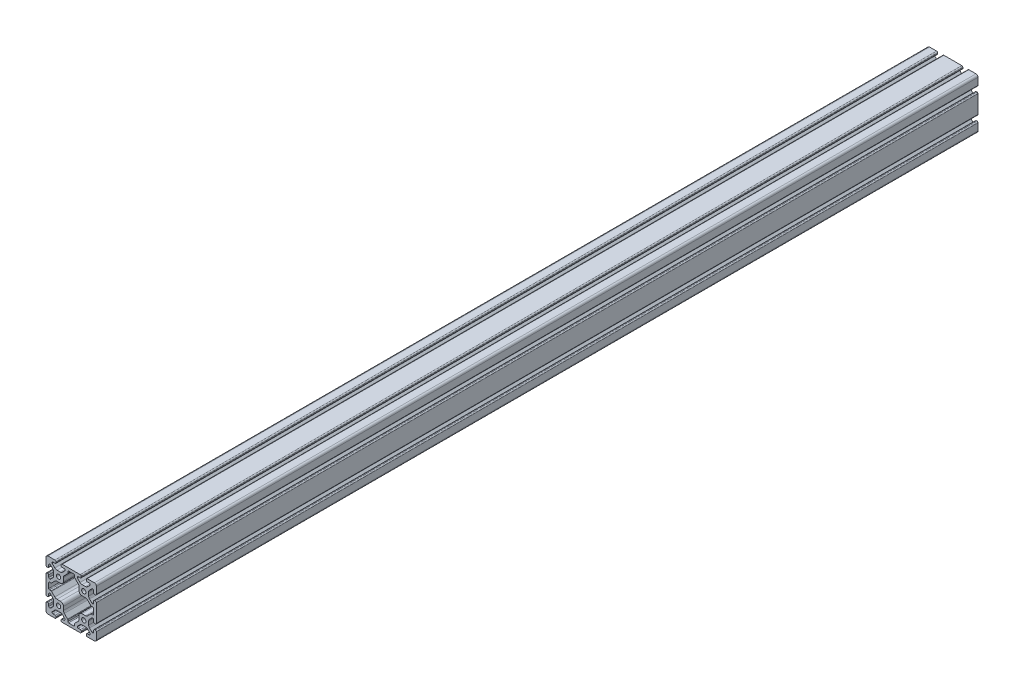
SolidWorks part; units mm, degrees
material "6061 Alloy"
ref_plane "Front Plane" through (0, 0, 0) normal (0, 0, 1) x (1, 0, 0)
ref_plane "Top Plane" through (0, 0, 0) normal (0, 1, 0) x (1, 0, 0)
ref_plane "Right Plane" through (0, 0, 0) normal (1, 0, 0) x (0, 0, -1)
sketch "Sketch1" plane through (0, 0, 0) normal (0, 0, 1) x (1, 0, 0)
  line L0 (0, -40) -> (0, 40) construction
  line L1 (0, 0) -> (-43.5804, 43.5804) construction
  line L2 (-20, 20) -> (-47.7323, 20) construction
  line L3 (-20, 20) -> (3.796, 43.796) construction
  line L4 (-20, 20) -> (-20, 43.5758) construction
  line L5 (-20, -27.7) -> (-20, -47.5576) construction
  line L7 (-36.8718, 24) -> (-28.8718, 24) construction
  line L8 (-36.8718, 24) -> (-36.8718, 16) construction
  line L9 (-36.8718, 16) -> (-28.8718, 16) construction
  line L10 (-28.8718, 24) -> (-28.8718, 16) construction
  line L11 (-36.8718, 24) -> (-28.8718, 16) construction
  line L12 (-36.8718, 16) -> (-28.8718, 24) construction
  line L131 (29.0912, 26.0365) -> (33.0827, 30.028)
  line L132 (27.7, 17.3222) -> (27.7, 22.6778)
  line L133 (29.0912, 13.9635) -> (33.0827, 9.972)
  line L134 (33.6201, 9.7494) -> (34.11, 9.7494)
  line L135 (35.68, 11.3194) -> (35.68, 14.2221)
  line L136 (37.25, 15.7921) -> (38.43, 15.7921)
  line L137 (40, 14.2221) -> (40, 7.0214)
  line L138 (40, 7.0214) -> (40, -7.0214)
  line L139 (40, -7.0214) -> (40, -14.2221)
  line L140 (38.43, -15.7921) -> (37.25, -15.7921)
  line L141 (35.68, -14.2221) -> (35.68, -11.3194)
  line L142 (33.6201, -9.7494) -> (34.11, -9.7494)
  line L143 (29.0912, -13.9635) -> (33.0827, -9.972)
  line L144 (27.7, -22.6778) -> (27.7, -17.3222)
  line L145 (29.0912, -26.0365) -> (33.0827, -30.028)
  line L146 (33.6201, -30.2506) -> (34.11, -30.2506)
  line L147 (35.68, -28.6806) -> (35.68, -25.7779)
  line L148 (37.25, -24.2079) -> (38.43, -24.2079)
  line L149 (40, -25.7779) -> (40, -33.0259)
  line L150 (40, -33.0259) -> (40, -36.83)
  line L151 (36.83, -40) -> (32.9998, -40)
  line L152 (32.9998, -40) -> (25.5696, -40)
  line L153 (23.9996, -38.43) -> (23.9996, -37.25)
  line L154 (25.5696, -35.68) -> (28.4723, -35.68)
  line L155 (30.0413, -34.0552) -> (30.0171, -33.3605)
  line L156 (29.7949, -32.8496) -> (26.0365, -29.0912)
  line L157 (17.3222, -27.7) -> (22.6778, -27.7)
  line L158 (10.035, -33.0197) -> (13.9635, -29.0912)
  line L159 (9.8124, -33.8926) -> (9.8124, -33.5571)
  line L160 (11.3824, -35.4626) -> (14.4246, -35.4626)
  line L161 (15.9946, -37.0326) -> (15.9946, -38.43)
  line L162 (14.4246, -40) -> (6.9987, -40)
  line L163 (6.9987, -40) -> (-6.9987, -40)
  line L164 (-6.9987, -40) -> (-14.4292, -40)
  line L165 (-15.9992, -38.43) -> (-15.9992, -37.25)
  line L166 (-14.4292, -35.68) -> (-11.5265, -35.68)
  line L167 (-9.9574, -34.0552) -> (-9.9816, -33.3618)
  line L168 (-10.2038, -32.8509) -> (-13.9635, -29.0912)
  line L169 (-22.6778, -27.7) -> (-17.3222, -27.7)
  line L170 (-30.028, -33.0827) -> (-26.0365, -29.0912)
  line L171 (-30.2506, -34.11) -> (-30.2506, -33.6201)
  line L172 (-28.6806, -35.68) -> (-25.7231, -35.68)
  line L173 (-24.1531, -37.25) -> (-24.1531, -38.43)
  line L174 (-25.7231, -40) -> (-33, -40)
  line L175 (-33, -40) -> (-36.83, -40)
  line L176 (-40, -36.83) -> (-40, -33.0191)
  line L177 (-40, -33.0191) -> (-40, -25.591)
  line L178 (-38.43, -24.021) -> (-37.25, -24.021)
  line L179 (-35.68, -28.4937) -> (-35.68, -25.591)
  line L180 (-34.0552, -30.0627) -> (-33.3827, -30.0392)
  line L181 (-32.8718, -29.8171) -> (-29.0912, -26.0365)
  line L182 (-27.7, -22.6778) -> (-27.7, -17.3222)
  line L183 (-29.0912, -13.9635) -> (-33.0827, -9.972)
  line L184 (-34.11, -9.7494) -> (-33.6201, -9.7494)
  line L185 (-35.68, -11.3194) -> (-35.68, -14.4473)
  line L186 (-38.43, -16.0173) -> (-37.25, -16.0173)
  line L187 (-40, -14.4473) -> (-40, -7.0169)
  line L188 (-40, -7.0169) -> (-40, 7.0169)
  line L189 (-40, 7.0169) -> (-40, 14.1348)
  line L190 (-38.1948, 15.94) -> (-36.9772, 15.94)
  line L191 (-35.68, 11.3194) -> (-35.68, 14.6428)
  line L192 (-34.11, 9.7494) -> (-33.6201, 9.7494)
  line L193 (-33.0827, 9.972) -> (-29.0912, 13.9635)
  line L194 (-27.7, 17.3222) -> (-27.7, 22.6778)
  line L195 (-29.0912, 26.0365) -> (-33.0827, 30.028)
  line L196 (-34.11, 30.2506) -> (-33.6201, 30.2506)
  line L197 (-35.68, 28.6806) -> (-35.68, 25.3572)
  line L198 (-38.1948, 24.06) -> (-36.9772, 24.06)
  line L199 (-40, 25.8652) -> (-40, 33.3181)
  line L200 (-40, 33.3181) -> (-40, 36.83)
  line L201 (-36.83, 40) -> (-33.0314, 40)
  line L202 (-33.0314, 40) -> (-25.8652, 40)
  line L203 (-24.06, 36.9772) -> (-24.06, 38.1948)
  line L204 (-25.3572, 35.68) -> (-28.7018, 35.68)
  line L205 (-30.285, 33.6069) -> (-30.285, 34.0968)
  line L206 (-30.0961, 33.1508) -> (-26.0365, 29.0912)
  line L207 (-22.6778, 27.7) -> (-17.3222, 27.7)
  line L208 (-13.9635, 29.0912) -> (-9.9039, 33.1508)
  line L209 (-9.715, 33.6069) -> (-9.715, 34.0968)
  line L210 (-14.6428, 35.68) -> (-11.2982, 35.68)
  line L211 (-15.94, 36.9772) -> (-15.94, 38.1948)
  line L212 (-14.1348, 40) -> (-6.9844, 40)
  line L213 (-6.9844, 40) -> (6.9844, 40)
  line L214 (6.9844, 40) -> (14.1348, 40)
  line L215 (15.94, 36.9772) -> (15.94, 38.1948)
  line L216 (14.6428, 35.68) -> (11.2982, 35.68)
  line L217 (9.715, 33.6069) -> (9.715, 34.0968)
  line L218 (9.9039, 33.1508) -> (13.9635, 29.0912)
  line L219 (17.3222, 27.7) -> (22.6778, 27.7)
  line L220 (26.0365, 29.0912) -> (30.028, 33.0827)
  line L221 (30.2506, 33.6201) -> (30.2506, 34.11)
  line L222 (25.5409, 35.679) -> (28.6258, 35.679)
  line L223 (23.9709, 37.249) -> (23.9709, 38.43)
  line L224 (25.5409, 40) -> (36.83, 40)
  line L226 (40, 36.83) -> (40, 32.9339)
  line L227 (40, 32.9339) -> (40, 25.7779)
  line L228 (38.43, 24.2079) -> (37.0956, 24.2079)
  line L229 (35.5256, 25.7779) -> (35.5256, 28.6806)
  line L230 (33.6201, 30.2506) -> (33.9556, 30.2506)
  line L231 (17.07, 12.32) -> (22.6578, 12.32)
  line L232 (26.0165, 10.9288) -> (31.1439, 5.8014)
  line L233 (32.0419, 5.4294) -> (34.41, 5.4294)
  line L234 (35.68, -4.1594) -> (35.68, 4.1594)
  line L235 (32.0419, -5.4294) -> (34.41, -5.4294)
  line L236 (26.0165, -10.9288) -> (31.1439, -5.8014)
  line L237 (17.07, -12.32) -> (22.6578, -12.32)
  line L238 (12.32, -22.6578) -> (12.32, -17.07)
  line L239 (5.8014, -31.1439) -> (10.9288, -26.0165)
  line L240 (5.4294, -34.41) -> (5.4294, -32.0419)
  line L241 (-4.1594, -35.68) -> (4.1594, -35.68)
  line L242 (-5.4294, -34.41) -> (-5.4294, -32.0419)
  line L243 (-5.8014, -31.1439) -> (-10.9288, -26.0165)
  line L244 (-12.32, -22.6578) -> (-12.32, -17.07)
  line L245 (-22.6578, -12.32) -> (-17.07, -12.32)
  line L246 (-26.0165, -10.9288) -> (-31.1439, -5.8014)
  line L247 (-34.41, -5.4294) -> (-32.0419, -5.4294)
  line L248 (-35.68, -4.1594) -> (-35.68, 4.1594)
  line L249 (-34.41, 5.4294) -> (-32.0419, 5.4294)
  line L250 (-31.1439, 5.8014) -> (-26.0165, 10.9288)
  line L251 (-22.6578, 12.32) -> (-17.07, 12.32)
  line L252 (-12.32, 17.07) -> (-12.32, 22.6578)
  line L253 (-10.9288, 26.0165) -> (-5.8014, 31.1439)
  line L254 (-5.4294, 32.0419) -> (-5.4294, 34.41)
  line L255 (-4.1594, 35.68) -> (4.1594, 35.68)
  line L256 (5.4294, 32.0419) -> (5.4294, 34.41)
  line L257 (5.8014, 31.1439) -> (10.9288, 26.0165)
  line L258 (12.32, 17.07) -> (12.32, 22.6578)
  line L260 (-40, 0) -> (40, 0) construction
  circle A0 centre (-32.8718, 20) radius 4 construction
  circle A116 centre (-20, 20) radius 3.4
  circle A117 centre (20, 20) radius 3.4
  circle A118 centre (20, -20) radius 3.4
  circle A119 centre (-20, -20) radius 3.4
  arc A120 (29.0912, 26.0365) -> (27.7, 22.6778) centre (32.45, 22.6778) ccw
  arc A121 (27.7, 17.3222) -> (29.0912, 13.9635) centre (32.45, 17.3222) ccw
  arc A122 (33.0827, 9.972) -> (33.6201, 9.7494) centre (33.6201, 10.5094) ccw
  arc A123 (34.11, 9.7494) -> (35.68, 11.3194) centre (34.11, 11.3194) ccw
  arc A124 (37.25, 15.7921) -> (35.68, 14.2221) centre (37.25, 14.2221) ccw
  arc A125 (40, 14.2221) -> (38.43, 15.7921) centre (38.43, 14.2221) ccw
  arc A126 (38.43, -15.7921) -> (40, -14.2221) centre (38.43, -14.2221) ccw
  arc A127 (35.68, -14.2221) -> (37.25, -15.7921) centre (37.25, -14.2221) ccw
  arc A128 (35.68, -11.3194) -> (34.11, -9.7494) centre (34.11, -11.3194) ccw
  arc A129 (33.6201, -9.7494) -> (33.0827, -9.972) centre (33.6201, -10.5094) ccw
  arc A130 (29.0912, -13.9635) -> (27.7, -17.3222) centre (32.45, -17.3222) ccw
  arc A131 (27.7, -22.6778) -> (29.0912, -26.0365) centre (32.45, -22.6778) ccw
  arc A132 (33.0827, -30.028) -> (33.6201, -30.2506) centre (33.6201, -29.4906) ccw
  arc A133 (34.11, -30.2506) -> (35.68, -28.6806) centre (34.11, -28.6806) ccw
  arc A134 (37.25, -24.2079) -> (35.68, -25.7779) centre (37.25, -25.7779) ccw
  arc A135 (40, -25.7779) -> (38.43, -24.2079) centre (38.43, -25.7779) ccw
  arc A136 (36.83, -40) -> (40, -36.83) centre (36.83, -36.83) ccw
  arc A137 (23.9996, -38.43) -> (25.5696, -40) centre (25.5696, -38.43) ccw
  arc A138 (25.5696, -35.68) -> (23.9996, -37.25) centre (25.5696, -37.25) ccw
  arc A139 (28.4723, -35.68) -> (30.0413, -34.0552) centre (28.4723, -34.11) ccw
  arc A140 (30.0171, -33.3605) -> (29.7949, -32.8496) centre (29.2575, -33.387) ccw
  arc A141 (26.0365, -29.0912) -> (22.6778, -27.7) centre (22.6778, -32.45) ccw
  arc A142 (17.3222, -27.7) -> (13.9635, -29.0912) centre (17.3222, -32.45) ccw
  arc A143 (10.035, -33.0197) -> (9.8124, -33.5571) centre (10.5724, -33.5571) ccw
  arc A144 (9.8124, -33.8926) -> (11.3824, -35.4626) centre (11.3824, -33.8926) ccw
  arc A145 (15.9946, -37.0326) -> (14.4246, -35.4626) centre (14.4246, -37.0326) ccw
  arc A146 (14.4246, -40) -> (15.9946, -38.43) centre (14.4246, -38.43) ccw
  arc A147 (-15.9992, -38.43) -> (-14.4292, -40) centre (-14.4292, -38.43) ccw
  arc A148 (-14.4292, -35.68) -> (-15.9992, -37.25) centre (-14.4292, -37.25) ccw
  arc A149 (-11.5265, -35.68) -> (-9.9574, -34.0552) centre (-11.5265, -34.11) ccw
  arc A150 (-9.9816, -33.3618) -> (-10.2038, -32.8509) centre (-10.7412, -33.3883) ccw
  arc A151 (-13.9635, -29.0912) -> (-17.3222, -27.7) centre (-17.3222, -32.45) ccw
  arc A152 (-22.6778, -27.7) -> (-26.0365, -29.0912) centre (-22.6778, -32.45) ccw
  arc A153 (-30.028, -33.0827) -> (-30.2506, -33.6201) centre (-29.4906, -33.6201) ccw
  arc A154 (-30.2506, -34.11) -> (-28.6806, -35.68) centre (-28.6806, -34.11) ccw
  arc A155 (-24.1531, -37.25) -> (-25.7231, -35.68) centre (-25.7231, -37.25) ccw
  arc A156 (-25.7231, -40) -> (-24.1531, -38.43) centre (-25.7231, -38.43) ccw
  arc A157 (-40, -36.83) -> (-36.83, -40) centre (-36.83, -36.83) ccw
  arc A158 (-38.43, -24.021) -> (-40, -25.591) centre (-38.43, -25.591) ccw
  arc A159 (-35.68, -25.591) -> (-37.25, -24.021) centre (-37.25, -25.591) ccw
  arc A160 (-35.68, -28.4937) -> (-34.0552, -30.0627) centre (-34.11, -28.4937) ccw
  arc A161 (-33.3827, -30.0392) -> (-32.8718, -29.8171) centre (-33.4092, -29.2797) ccw
  arc A162 (-29.0912, -26.0365) -> (-27.7, -22.6778) centre (-32.45, -22.6778) ccw
  arc A163 (-27.7, -17.3222) -> (-29.0912, -13.9635) centre (-32.45, -17.3222) ccw
  arc A164 (-33.0827, -9.972) -> (-33.6201, -9.7494) centre (-33.6201, -10.5094) ccw
  arc A165 (-34.11, -9.7494) -> (-35.68, -11.3194) centre (-34.11, -11.3194) ccw
  arc A166 (-37.25, -16.0173) -> (-35.68, -14.4473) centre (-37.25, -14.4473) ccw
  arc A167 (-40, -14.4473) -> (-38.43, -16.0173) centre (-38.43, -14.4473) ccw
  arc A168 (-38.1948, 15.94) -> (-40, 14.1348) centre (-38.1948, 14.1348) ccw
  arc A169 (-35.68, 14.6428) -> (-36.9772, 15.94) centre (-36.9772, 14.6428) ccw
  arc A170 (-35.68, 11.3194) -> (-34.11, 9.7494) centre (-34.11, 11.3194) ccw
  arc A171 (-33.6201, 9.7494) -> (-33.0827, 9.972) centre (-33.6201, 10.5094) ccw
  arc A172 (-29.0912, 13.9635) -> (-27.7, 17.3222) centre (-32.45, 17.3222) ccw
  arc A173 (-27.7, 22.6778) -> (-29.0912, 26.0365) centre (-32.45, 22.6778) ccw
  arc A174 (-33.0827, 30.028) -> (-33.6201, 30.2506) centre (-33.6201, 29.4906) ccw
  arc A175 (-34.11, 30.2506) -> (-35.68, 28.6806) centre (-34.11, 28.6806) ccw
  arc A176 (-36.9772, 24.06) -> (-35.68, 25.3572) centre (-36.9772, 25.3572) ccw
  arc A177 (-40, 25.8652) -> (-38.1948, 24.06) centre (-38.1948, 25.8652) ccw
  arc A178 (-36.83, 40) -> (-40, 36.83) centre (-36.83, 36.83) ccw
  arc A179 (-24.06, 38.1948) -> (-25.8652, 40) centre (-25.8652, 38.1948) ccw
  arc A180 (-25.3572, 35.68) -> (-24.06, 36.9772) centre (-25.3572, 36.9772) ccw
  arc A181 (-28.7018, 35.68) -> (-30.285, 34.0968) centre (-28.7018, 34.0968) ccw
  arc A182 (-30.285, 33.6069) -> (-30.0961, 33.1508) centre (-29.6399, 33.6069) ccw
  arc A183 (-26.0365, 29.0912) -> (-22.6778, 27.7) centre (-22.6778, 32.45) ccw
  arc A184 (-17.3222, 27.7) -> (-13.9635, 29.0912) centre (-17.3222, 32.45) ccw
  arc A185 (-9.9039, 33.1508) -> (-9.715, 33.6069) centre (-10.3601, 33.6069) ccw
  arc A186 (-9.715, 34.0968) -> (-11.2982, 35.68) centre (-11.2982, 34.0968) ccw
  arc A187 (-15.94, 36.9772) -> (-14.6428, 35.68) centre (-14.6428, 36.9772) ccw
  arc A188 (-14.1348, 40) -> (-15.94, 38.1948) centre (-14.1348, 38.1948) ccw
  arc A189 (15.94, 38.1948) -> (14.1348, 40) centre (14.1348, 38.1948) ccw
  arc A190 (14.6428, 35.68) -> (15.94, 36.9772) centre (14.6428, 36.9772) ccw
  arc A191 (11.2982, 35.68) -> (9.715, 34.0968) centre (11.2982, 34.0968) ccw
  arc A192 (9.715, 33.6069) -> (9.9039, 33.1508) centre (10.3601, 33.6069) ccw
  arc A193 (13.9635, 29.0912) -> (17.3222, 27.7) centre (17.3222, 32.45) ccw
  arc A194 (22.6778, 27.7) -> (26.0365, 29.0912) centre (22.6778, 32.45) ccw
  arc A195 (30.028, 33.0827) -> (30.2506, 33.6201) centre (29.4906, 33.6201) ccw
  arc A196 (30.2506, 34.11) -> (28.6258, 35.679) centre (28.6806, 34.11) ccw
  arc A197 (23.9709, 37.249) -> (25.5409, 35.679) centre (25.5409, 37.249) ccw
  arc A198 (25.5409, 40) -> (23.9709, 38.43) centre (25.5409, 38.43) ccw
  arc A199 (40, 36.83) -> (36.83, 40) centre (36.83, 36.83) ccw
  arc A200 (38.43, 24.2079) -> (40, 25.7779) centre (38.43, 25.7779) ccw
  arc A201 (35.5256, 25.7779) -> (37.0956, 24.2079) centre (37.0956, 25.7779) ccw
  arc A202 (35.5256, 28.6806) -> (33.9556, 30.2506) centre (33.9556, 28.6806) ccw
  arc A203 (33.6201, 30.2506) -> (33.0827, 30.028) centre (33.6201, 29.4906) ccw
  arc A204 (26.0165, 10.9288) -> (22.6578, 12.32) centre (22.6578, 7.57) ccw
  arc A205 (31.1439, 5.8014) -> (32.0419, 5.4294) centre (32.0419, 6.6994) ccw
  arc A206 (35.68, 4.1594) -> (34.41, 5.4294) centre (34.41, 4.1594) ccw
  arc A207 (34.41, -5.4294) -> (35.68, -4.1594) centre (34.41, -4.1594) ccw
  arc A208 (32.0419, -5.4294) -> (31.1439, -5.8014) centre (32.0419, -6.6994) ccw
  arc A209 (22.6578, -12.32) -> (26.0165, -10.9288) centre (22.6578, -7.57) ccw
  arc A210 (17.07, -12.32) -> (12.32, -17.07) centre (17.07, -17.07) ccw
  arc A211 (10.9288, -26.0165) -> (12.32, -22.6578) centre (7.57, -22.6578) ccw
  arc A212 (5.8014, -31.1439) -> (5.4294, -32.0419) centre (6.6994, -32.0419) ccw
  arc A213 (4.1594, -35.68) -> (5.4294, -34.41) centre (4.1594, -34.41) ccw
  arc A214 (-5.4294, -34.41) -> (-4.1594, -35.68) centre (-4.1594, -34.41) ccw
  arc A215 (-5.4294, -32.0419) -> (-5.8014, -31.1439) centre (-6.6994, -32.0419) ccw
  arc A216 (-12.32, -22.6578) -> (-10.9288, -26.0165) centre (-7.57, -22.6578) ccw
  arc A217 (-12.32, -17.07) -> (-17.07, -12.32) centre (-17.07, -17.07) ccw
  arc A218 (-26.0165, -10.9288) -> (-22.6578, -12.32) centre (-22.6578, -7.57) ccw
  arc A219 (-31.1439, -5.8014) -> (-32.0419, -5.4294) centre (-32.0419, -6.6994) ccw
  arc A220 (-35.68, -4.1594) -> (-34.41, -5.4294) centre (-34.41, -4.1594) ccw
  arc A221 (-34.41, 5.4294) -> (-35.68, 4.1594) centre (-34.41, 4.1594) ccw
  arc A222 (-32.0419, 5.4294) -> (-31.1439, 5.8014) centre (-32.0419, 6.6994) ccw
  arc A223 (-22.6578, 12.32) -> (-26.0165, 10.9288) centre (-22.6578, 7.57) ccw
  arc A224 (-17.07, 12.32) -> (-12.32, 17.07) centre (-17.07, 17.07) ccw
  arc A225 (-10.9288, 26.0165) -> (-12.32, 22.6578) centre (-7.57, 22.6578) ccw
  arc A226 (-5.8014, 31.1439) -> (-5.4294, 32.0419) centre (-6.6994, 32.0419) ccw
  arc A227 (-4.1594, 35.68) -> (-5.4294, 34.41) centre (-4.1594, 34.41) ccw
  arc A228 (5.4294, 34.41) -> (4.1594, 35.68) centre (4.1594, 34.41) ccw
  arc A229 (5.4294, 32.0419) -> (5.8014, 31.1439) centre (6.6994, 32.0419) ccw
  arc A230 (12.32, 22.6578) -> (10.9288, 26.0165) centre (7.57, 22.6578) ccw
  arc A231 (12.32, 17.07) -> (17.07, 12.32) centre (17.07, 17.07) ccw
  point P9 (-32.8718, 20)
  dimension "D8" = 6.8
  dimension "D1" = 80
  dimension "D2" = 40
  dimension "D3" = 20
  dimension "D4" = 20.57
  dimension "D5" = 4.32
  dimension "D6" = 4.32
  dimension "D7" = 8.12
  dimension "D9" = 4.32
  dimension "D10" = 12.3
  dimension "D11" = 8
  dimension "D12" = 8
extrude "Extrude1" add sketch "Sketch1" against normal blind 1400
